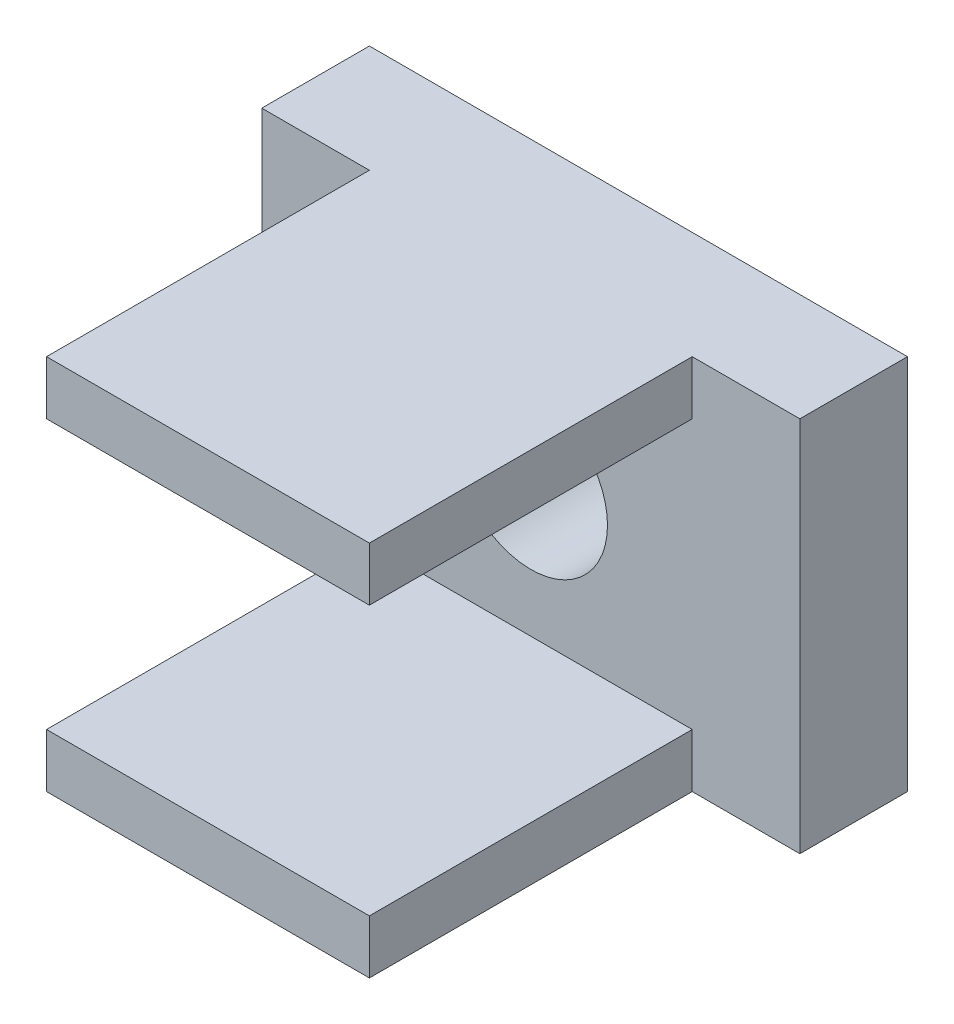
SolidWorks part; units mm, degrees
ref_plane "Front Plane" through (0, 0, 0) normal (0, 0, 1) x (1, 0, 0)
ref_plane "Top Plane" through (0, 0, 0) normal (0, 1, 0) x (1, 0, 0)
ref_plane "Right Plane" through (0, 0, 0) normal (1, 0, 0) x (0, 0, -1)
sketch "Sketch1" plane through (0, 0, 0) normal (0, 0, 1) x (1, 0, 0)
  line L1 (5, -3.5) -> (-5, -3.5)
  line L2 (5, -3.5) -> (5, 3.5)
  line L3 (5, 3.5) -> (-5, 3.5)
  line L4 (-5, -3.5) -> (-5, 3.5)
  line L5 (5, -3.5) -> (-5, 3.5) construction
  line L6 (5, 3.5) -> (-5, -3.5) construction
  point P0 (0, 0)
  dimension "D1" = 10
  dimension "D2" = 7
extrude "Boss-Extrude1" add sketch "Sketch1" along normal blind 2
sketch "Sketch2" plane through (0, 0, 2) normal (0, 0, 1) x (1, 0, 0)
  circle A0 centre (0, 0) radius 1.425
  dimension "D1" = 2.85
extrude "Cut-Extrude1" cut sketch "Sketch2" against normal through all
sketch "Sketch3" plane through (0, 0, 2) normal (0, 0, 1) x (1, 0, 0)
  line L0 (5, 3.5) -> (-5, 3.5) construction
  line L1 (-3, 3.5) -> (3, 3.5)
  line L2 (-3, 3.5) -> (-3, 2.5)
  line L3 (-3, 2.5) -> (3, 2.5)
  line L4 (3, 3.5) -> (3, 2.5)
  line L5 (0, 0) -> (0, 3.5) construction
  dimension "D1" = 6
  dimension "D2" = 1
extrude "Boss-Extrude2" add sketch "Sketch3" along normal blind 6
mirror "Mirror1" about plane through (0, 0, 0) normal (0, 1, 0) of "Boss-Extrude2"
